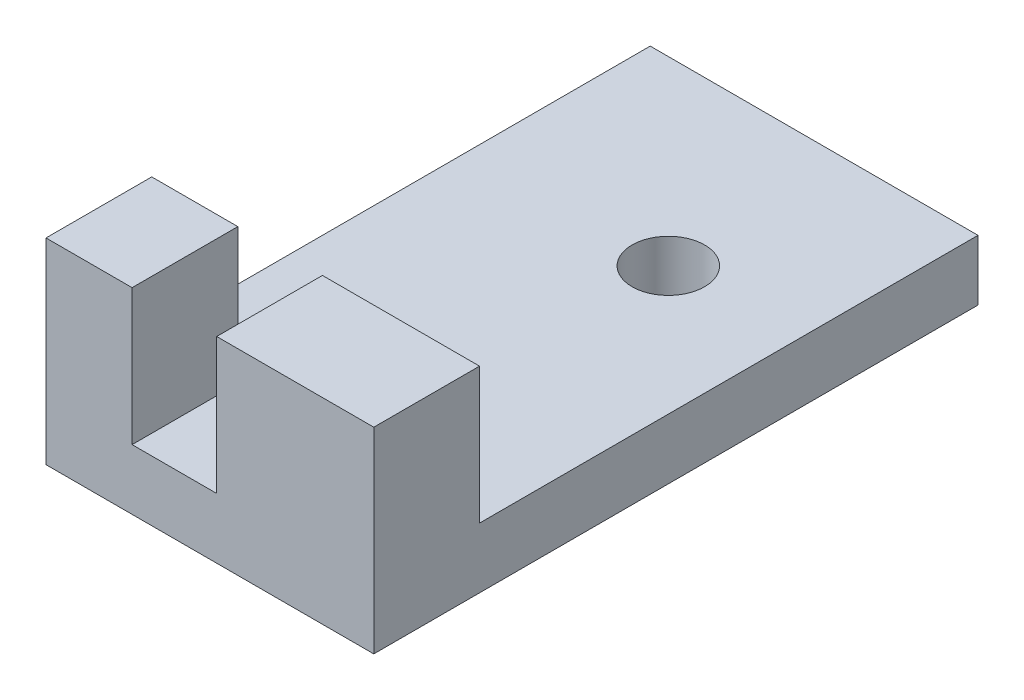
SolidWorks part; units mm, degrees
ref_plane "Front Plane" through (0, 0, 0) normal (0, 0, 1) x (1, 0, 0)
ref_plane "Top Plane" through (0, 0, 0) normal (0, 1, 0) x (1, 0, 0)
ref_plane "Right Plane" through (0, 0, 0) normal (1, 0, 0) x (0, 0, -1)
sketch "Sketch1" plane through (0, 0, 0) normal (0, 1, 0) x (1, 0, 0)
  line L1 (0, 0) -> (21.7, 0)
  line L2 (0, 0) -> (0, -40)
  line L3 (0, -40) -> (21.7, -40)
  line L4 (21.7, 0) -> (21.7, -40)
  dimension "D1" = 40
  dimension "D2" = 21.7
extrude "Boss-Extrude1" add sketch "Sketch1" along normal blind 13
sketch "Sketch3" plane through (0, 13, 0) normal (0, 1, 0) x (1, 0, 0)
  line L0 (21.7, -40) -> (21.7, 0) construction
  line L1 (0, 0) -> (21.7, 0)
  line L2 (0, 0) -> (0, -33)
  line L3 (0, -33) -> (21.7, -33)
  line L4 (21.7, 0) -> (21.7, -33)
  dimension "D1" = 33
extrude "Cut-Extrude1" cut sketch "Sketch3" against normal blind 9
sketch "Sketch5" plane through (0, 0, 33) normal (0, 0, -1) x (-1, 0, 0)
  line L0 (0, 13) -> (-21.7, 13) construction
  line L1 (-11.3, 13) -> (-5.7, 13)
  line L2 (-11.3, 13) -> (-11.3, 4)
  line L3 (-11.3, 4) -> (-5.7, 4)
  line L4 (-5.7, 13) -> (-5.7, 4)
  line L5 (-21.7, 4) -> (-21.7, 13) construction
  dimension "D1" = 9
  dimension "D2" = 10.4
  dimension "D3" = 5.6
extrude "Cut-Extrude2" cut sketch "Sketch5" against normal through all
sketch "Sketch6" plane through (0, 4, 0) normal (0, 1, 0) x (1, 0, 0)
  line L0 (21.7, 0) -> (0, 0) construction
  line L1 (21.7, -33) -> (21.7, 0) construction
  line L2 (0, 0) -> (0, -33) construction
  circle A0 centre (13.2, -12) radius 2.4
  dimension "D1" = 4.8
  dimension "D2" = 12
  dimension "D3" = 8.5
  dimension "D4" = 13.2
extrude "Cut-Extrude4" cut sketch "Sketch6" against normal through all contours A0
